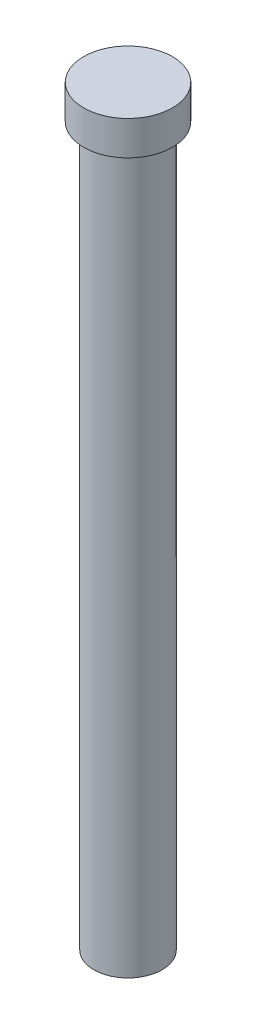
SolidWorks part; units mm, degrees
material "M2 HSS"
ref_plane "Front Plane" through (0, 0, 0) normal (0, 0, 1) x (1, 0, 0)
ref_plane "Top Plane" through (0, 0, 0) normal (0, 1, 0) x (1, 0, 0)
ref_plane "Right Plane" through (0, 0, 0) normal (1, 0, 0) x (0, 0, -1)
sketch "Sketch1" plane through (0, 0, 0) normal (0, 0, 1) x (1, 0, 0)
  line L0 (0, 0) -> (6.5, 0)
  line L2 (5, -5) -> (5, -110)
  line L3 (5, -110) -> (0, -110)
  line L4 (0, -110) -> (0, 0)
  line L5 (0, -115) -> (0, 5) construction
  line L6 (5, -5) -> (6.5, -5)
  line L7 (6.5, -5) -> (6.5, 0)
  dimension "D1" = 5
  dimension "D2" = 5
  dimension "D3" = 10
  dimension "D4" = 13
  dimension "D5" = 5
  dimension "D6" = 110
revolve "Revolve1" add sketch "Sketch1" angle 360 about L5
